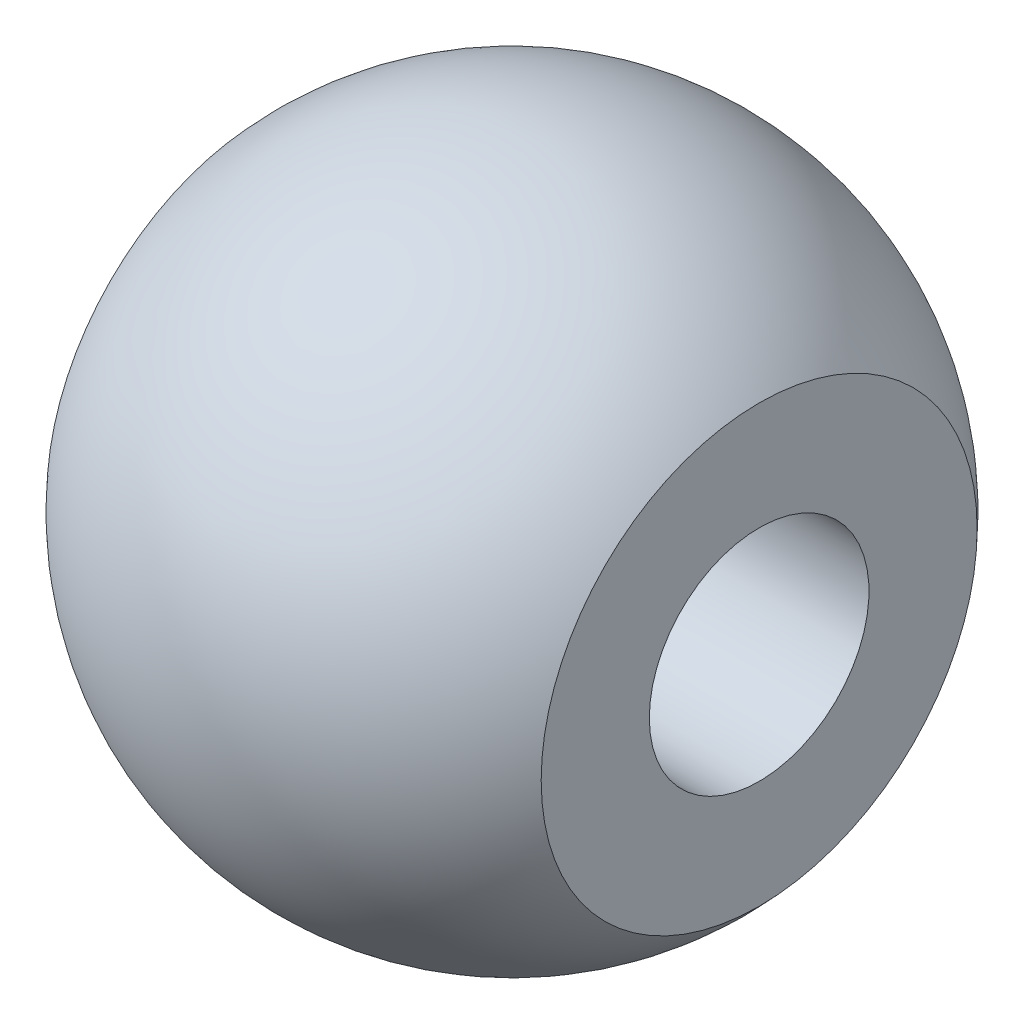
SolidWorks part; units mm, degrees
ref_plane "Front Plane" through (0, 0, 0) normal (0, 0, 1) x (1, 0, 0)
ref_plane "Top Plane" through (0, 0, 0) normal (0, 1, 0) x (1, 0, 0)
ref_plane "Right Plane" through (0, 0, 0) normal (1, 0, 0) x (0, 0, -1)
sketch "Sketch1" plane through (0, 0, 0) normal (0, 0, 1) x (1, 0, 0)
  line L0 (4.5, 0) -> (-3.5, 0)
  line L1 (-4.5, 3.9686) -> (-4.5, 3)
  line L2 (4.5, 3.9686) -> (4.5, 0)
  line L3 (-3.5, 2) -> (-4.5, 3)
  line L5 (-3.5, 0) -> (-3.5, 2)
  arc A0 (-4.5, 3.9686) -> (4.5, 3.9686) centre (0, 0) cw
  dimension "D1" = 45
  dimension "D4" = 6
  dimension "D2" = 1
revolve "Revolve1" add sketch "Sketch1" angle 360 about L0
sketch "Sketch2" plane through (-3.5, 0, 0) normal (-1, 0, 0) x (0, 0, 1)
  circle A0 centre (0, 0) radius 2
extrude "Cut-Extrude1" cut sketch "Sketch2" against normal through all
